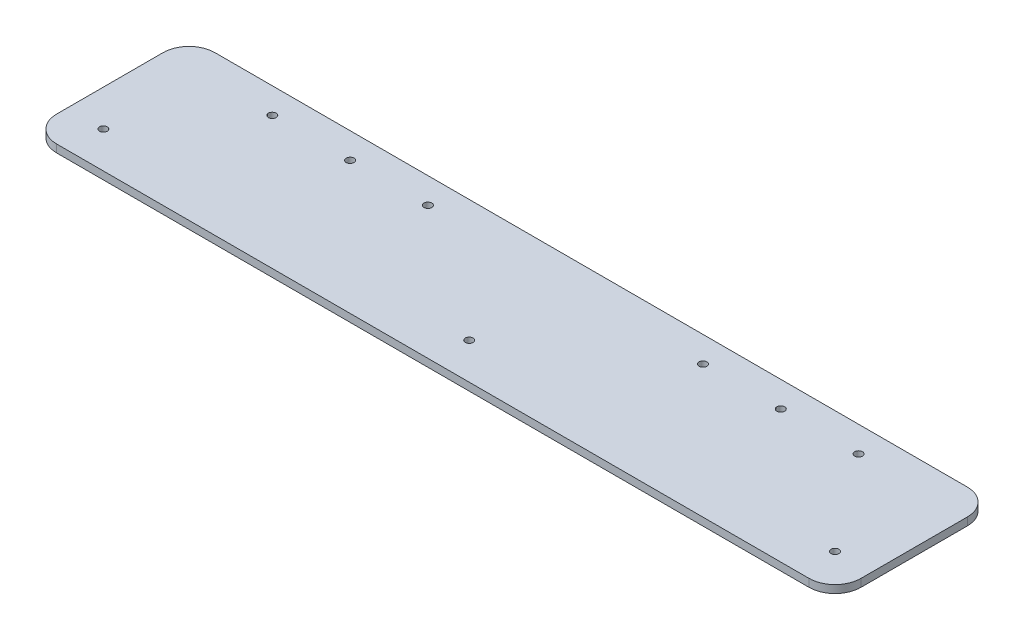
SolidWorks part; units mm, degrees
ref_plane "前视基准面" through (0, 0, 0) normal (0, 0, 1) x (1, 0, 0)
ref_plane "上视基准面" through (0, 0, 0) normal (0, 1, 0) x (1, 0, 0)
ref_plane "右视基准面" through (0, 0, 0) normal (1, 0, 0) x (0, 0, -1)
sketch "草图1" plane through (0, 0, 0) normal (0, 1, 0) x (1, 0, 0)
  line L0 (183.25, -128.5) -> (183.25, -131.5) construction
  line L1 (10, 0) -> (136.8844, 0) construction
  line L2 (0, -10) -> (0, -210) construction
  line L3 (10, -220) -> (300, -220)
  line L4 (310, -10) -> (310, -210) construction
  line L5 (28.75, -14.75) -> (47.25, -14.75) construction
  line L6 (28.75, -14.75) -> (28.75, -33.25) construction
  line L7 (28.75, -33.25) -> (47.25, -33.25) construction
  line L8 (173, -85) -> (173, 0) construction
  line L9 (173, -85) -> (310, -85) construction
  line L10 (190, -66) -> (190, 0) construction
  line L11 (215, -58) -> (215, 0) construction
  line L12 (241, -58) -> (241, 0) construction
  line L13 (247, -84) -> (247, 0) construction
  line L14 (222, -84) -> (222, 0) construction
  line L15 (0, -220) -> (310, 0) construction
  line L16 (241, -58) -> (310, -58) construction
  line L17 (247, -84) -> (310, -84) construction
  line L18 (215, -58) -> (310, -58) construction
  line L19 (222, -84) -> (310, -84) construction
  line L20 (190, -66) -> (310, -66) construction
  line L21 (310, -220) -> (0, 0) construction
  line L22 (141.1791, -3.5) -> (143.5, -3.5) construction
  line L23 (139.4291, -2.4682) -> (138.6344, -1.0318) construction
  line L24 (170.5709, -2.4682) -> (171.3656, -1.0318) construction
  line L25 (173.1156, 0) -> (300, 0) construction
  line L26 (155, -110) -> (155, -220) construction
  line L27 (47.25, -14.75) -> (47.25, -33.25) construction
  line L28 (28.75, -14.75) -> (47.25, -33.25) construction
  line L29 (28.75, -33.25) -> (47.25, -14.75) construction
  line L30 (52.75, -14.75) -> (71.25, -14.75) construction
  line L31 (52.75, -14.75) -> (52.75, -33.25) construction
  line L32 (52.75, -33.25) -> (71.25, -33.25) construction
  line L33 (71.25, -14.75) -> (71.25, -33.25) construction
  line L34 (52.75, -14.75) -> (71.25, -33.25) construction
  line L35 (52.75, -33.25) -> (71.25, -14.75) construction
  line L36 (76.75, -14.75) -> (95.25, -14.75) construction
  line L37 (76.75, -14.75) -> (76.75, -33.25) construction
  line L38 (76.75, -33.25) -> (95.25, -33.25) construction
  line L39 (95.25, -14.75) -> (95.25, -33.25) construction
  line L40 (76.75, -14.75) -> (95.25, -33.25) construction
  line L41 (76.75, -33.25) -> (95.25, -14.75) construction
  line L42 (100.75, -14.75) -> (119.25, -14.75) construction
  line L43 (100.75, -14.75) -> (100.75, -33.25) construction
  line L44 (100.75, -33.25) -> (119.25, -33.25) construction
  line L45 (119.25, -14.75) -> (119.25, -33.25) construction
  line L46 (100.75, -14.75) -> (119.25, -33.25) construction
  line L47 (100.75, -33.25) -> (119.25, -14.75) construction
  line L48 (188.75, -14.75) -> (207.25, -14.75) construction
  line L49 (188.75, -14.75) -> (188.75, -33.25) construction
  line L50 (188.75, -33.25) -> (207.25, -33.25) construction
  line L51 (207.25, -14.75) -> (207.25, -33.25) construction
  line L52 (188.75, -14.75) -> (207.25, -33.25) construction
  line L53 (188.75, -33.25) -> (207.25, -14.75) construction
  line L54 (212.75, -14.75) -> (231.25, -14.75) construction
  line L55 (212.75, -14.75) -> (212.75, -33.25) construction
  line L56 (212.75, -33.25) -> (231.25, -33.25) construction
  line L57 (231.25, -14.75) -> (231.25, -33.25) construction
  line L58 (212.75, -14.75) -> (231.25, -33.25) construction
  line L59 (212.75, -33.25) -> (231.25, -14.75) construction
  line L60 (236.75, -14.75) -> (255.25, -14.75) construction
  line L61 (236.75, -14.75) -> (236.75, -33.25) construction
  line L62 (236.75, -33.25) -> (255.25, -33.25) construction
  line L63 (255.25, -14.75) -> (255.25, -33.25) construction
  line L64 (236.75, -14.75) -> (255.25, -33.25) construction
  line L65 (236.75, -33.25) -> (255.25, -14.75) construction
  line L66 (260.75, -14.75) -> (279.25, -14.75) construction
  line L67 (260.75, -14.75) -> (260.75, -33.25) construction
  line L68 (260.75, -33.25) -> (279.25, -33.25) construction
  line L69 (279.25, -14.75) -> (279.25, -33.25) construction
  line L70 (260.75, -14.75) -> (279.25, -33.25) construction
  line L71 (260.75, -33.25) -> (279.25, -14.75) construction
  line L72 (183, -123) -> (197, -123) construction
  line L73 (183, -123) -> (183, -128.25) construction
  line L74 (183, -137) -> (197, -137) construction
  line L75 (197, -123) -> (197, -128.25) construction
  line L76 (183, -123) -> (197, -137) construction
  line L77 (183, -137) -> (197, -123) construction
  line L78 (183.25, -128.5) -> (183, -128.25) construction
  line L79 (183.25, -131.5) -> (183, -131.75) construction
  line L80 (196.75, -128.5) -> (196.75, -131.5) construction
  line L81 (196.75, -128.5) -> (197, -128.25) construction
  line L82 (196.75, -131.5) -> (197, -131.75) construction
  line L83 (183, -131.75) -> (183, -137) construction
  line L84 (197, -131.75) -> (197, -137) construction
  line L85 (31.25, -22.5) -> (31.25, -25.5) construction
  line L86 (31, -17) -> (45, -17) construction
  line L87 (31, -17) -> (31, -22.25) construction
  line L88 (31, -31) -> (45, -31) construction
  line L89 (45, -17) -> (45, -22.25) construction
  line L90 (31, -17) -> (45, -31) construction
  line L91 (31, -31) -> (45, -17) construction
  line L92 (31.25, -22.5) -> (31, -22.25) construction
  line L93 (31.25, -25.5) -> (31, -25.75) construction
  line L94 (44.75, -22.5) -> (44.75, -25.5) construction
  line L95 (44.75, -22.5) -> (45, -22.25) construction
  line L96 (44.75, -25.5) -> (45, -25.75) construction
  line L97 (31, -25.75) -> (31, -31) construction
  line L98 (45, -25.75) -> (45, -31) construction
  line L99 (55.25, -22.5) -> (55.25, -25.5) construction
  line L100 (55, -17) -> (69, -17) construction
  line L101 (55, -17) -> (55, -22.25) construction
  line L102 (55, -31) -> (69, -31) construction
  line L103 (69, -17) -> (69, -22.25) construction
  line L104 (55, -17) -> (69, -31) construction
  line L105 (55, -31) -> (69, -17) construction
  line L106 (55.25, -22.5) -> (55, -22.25) construction
  line L107 (55.25, -25.5) -> (55, -25.75) construction
  line L108 (68.75, -22.5) -> (68.75, -25.5) construction
  line L109 (68.75, -22.5) -> (69, -22.25) construction
  line L110 (68.75, -25.5) -> (69, -25.75) construction
  line L111 (55, -25.75) -> (55, -31) construction
  line L112 (69, -25.75) -> (69, -31) construction
  line L113 (79.25, -22.5) -> (79.25, -25.5) construction
  line L114 (79, -17) -> (93, -17) construction
  line L115 (79, -17) -> (79, -22.25) construction
  line L116 (79, -31) -> (93, -31) construction
  line L117 (93, -17) -> (93, -22.25) construction
  line L118 (79, -17) -> (93, -31) construction
  line L119 (79, -31) -> (93, -17) construction
  line L120 (79.25, -22.5) -> (79, -22.25) construction
  line L121 (79.25, -25.5) -> (79, -25.75) construction
  line L122 (92.75, -22.5) -> (92.75, -25.5) construction
  line L123 (92.75, -22.5) -> (93, -22.25) construction
  line L124 (92.75, -25.5) -> (93, -25.75) construction
  line L125 (79, -25.75) -> (79, -31) construction
  line L126 (93, -25.75) -> (93, -31) construction
  line L127 (103.25, -22.5) -> (103.25, -25.5) construction
  line L128 (103, -17) -> (117, -17) construction
  line L129 (103, -17) -> (103, -22.25) construction
  line L130 (103, -31) -> (117, -31) construction
  line L131 (117, -17) -> (117, -22.25) construction
  line L132 (103, -17) -> (117, -31) construction
  line L133 (103, -31) -> (117, -17) construction
  line L134 (103.25, -22.5) -> (103, -22.25) construction
  line L135 (103.25, -25.5) -> (103, -25.75) construction
  line L136 (116.75, -22.5) -> (116.75, -25.5) construction
  line L137 (116.75, -22.5) -> (117, -22.25) construction
  line L138 (116.75, -25.5) -> (117, -25.75) construction
  line L139 (103, -25.75) -> (103, -31) construction
  line L140 (117, -25.75) -> (117, -31) construction
  line L141 (191.25, -22.5) -> (191.25, -25.5) construction
  line L142 (191, -17) -> (205, -17) construction
  line L143 (191, -17) -> (191, -22.25) construction
  line L144 (191, -31) -> (205, -31) construction
  line L145 (205, -17) -> (205, -22.25) construction
  line L146 (191, -17) -> (205, -31) construction
  line L147 (191, -31) -> (205, -17) construction
  line L148 (191.25, -22.5) -> (191, -22.25) construction
  line L149 (191.25, -25.5) -> (191, -25.75) construction
  line L150 (204.75, -22.5) -> (204.75, -25.5) construction
  line L151 (204.75, -22.5) -> (205, -22.25) construction
  line L152 (204.75, -25.5) -> (205, -25.75) construction
  line L153 (191, -25.75) -> (191, -31) construction
  line L154 (205, -25.75) -> (205, -31) construction
  line L155 (215.25, -22.5) -> (215.25, -25.5) construction
  line L156 (215, -17) -> (229, -17) construction
  line L157 (215, -17) -> (215, -22.25) construction
  line L158 (215, -31) -> (229, -31) construction
  line L159 (229, -17) -> (229, -22.25) construction
  line L160 (215, -17) -> (229, -31) construction
  line L161 (215, -31) -> (229, -17) construction
  line L162 (215.25, -22.5) -> (215, -22.25) construction
  line L163 (215.25, -25.5) -> (215, -25.75) construction
  line L164 (228.75, -22.5) -> (228.75, -25.5) construction
  line L165 (228.75, -22.5) -> (229, -22.25) construction
  line L166 (228.75, -25.5) -> (229, -25.75) construction
  line L167 (215, -25.75) -> (215, -31) construction
  line L168 (229, -25.75) -> (229, -31) construction
  line L169 (239.25, -22.5) -> (239.25, -25.5) construction
  line L170 (239, -17) -> (253, -17) construction
  line L171 (239, -17) -> (239, -22.25) construction
  line L172 (239, -31) -> (253, -31) construction
  line L173 (253, -17) -> (253, -22.25) construction
  line L174 (239, -17) -> (253, -31) construction
  line L175 (239, -31) -> (253, -17) construction
  line L176 (239.25, -22.5) -> (239, -22.25) construction
  line L177 (239.25, -25.5) -> (239, -25.75) construction
  line L178 (252.75, -22.5) -> (252.75, -25.5) construction
  line L179 (252.75, -22.5) -> (253, -22.25) construction
  line L180 (252.75, -25.5) -> (253, -25.75) construction
  line L181 (239, -25.75) -> (239, -31) construction
  line L182 (253, -25.75) -> (253, -31) construction
  line L183 (263.25, -22.5) -> (263.25, -25.5) construction
  line L184 (263, -17) -> (277, -17) construction
  line L185 (263, -17) -> (263, -22.25) construction
  line L186 (263, -31) -> (277, -31) construction
  line L187 (277, -17) -> (277, -22.25) construction
  line L188 (263, -17) -> (277, -31) construction
  line L189 (263, -31) -> (277, -17) construction
  line L190 (263.25, -22.5) -> (263, -22.25) construction
  line L191 (263.25, -25.5) -> (263, -25.75) construction
  line L192 (276.75, -22.5) -> (276.75, -25.5) construction
  line L193 (276.75, -22.5) -> (277, -22.25) construction
  line L194 (276.75, -25.5) -> (277, -25.75) construction
  line L195 (263, -25.75) -> (263, -31) construction
  line L196 (277, -25.75) -> (277, -31) construction
  line L197 (259.25, -64.5) -> (259.25, -67.5) construction
  line L198 (259, -59) -> (273, -59) construction
  line L199 (259, -59) -> (259, -64.25) construction
  line L200 (259, -73) -> (273, -73) construction
  line L201 (273, -59) -> (273, -64.25) construction
  line L202 (259, -59) -> (273, -73) construction
  line L203 (259, -73) -> (273, -59) construction
  line L204 (259.25, -64.5) -> (259, -64.25) construction
  line L205 (259.25, -67.5) -> (259, -67.75) construction
  line L206 (272.75, -64.5) -> (272.75, -67.5) construction
  line L207 (272.75, -64.5) -> (273, -64.25) construction
  line L208 (272.75, -67.5) -> (273, -67.75) construction
  line L209 (259, -67.75) -> (259, -73) construction
  line L210 (273, -67.75) -> (273, -73) construction
  line L211 (240.25, -82.5) -> (240.25, -85.5) construction
  line L212 (240, -77) -> (254, -77) construction
  line L213 (240, -77) -> (240, -82.25) construction
  line L214 (240, -91) -> (254, -91) construction
  line L215 (254, -77) -> (254, -82.25) construction
  line L216 (240, -77) -> (254, -91) construction
  line L217 (240, -91) -> (254, -77) construction
  line L218 (240.25, -82.5) -> (240, -82.25) construction
  line L219 (240.25, -85.5) -> (240, -85.75) construction
  line L220 (253.75, -82.5) -> (253.75, -85.5) construction
  line L221 (253.75, -82.5) -> (254, -82.25) construction
  line L222 (253.75, -85.5) -> (254, -85.75) construction
  line L223 (240, -85.75) -> (240, -91) construction
  line L224 (254, -85.75) -> (254, -91) construction
  line L225 (234.25, -56.5) -> (234.25, -59.5) construction
  line L226 (234, -51) -> (248, -51) construction
  line L227 (234, -51) -> (234, -56.25) construction
  line L228 (234, -65) -> (248, -65) construction
  line L229 (248, -51) -> (248, -56.25) construction
  line L230 (234, -51) -> (248, -65) construction
  line L231 (234, -65) -> (248, -51) construction
  line L232 (234.25, -56.5) -> (234, -56.25) construction
  line L233 (234.25, -59.5) -> (234, -59.75) construction
  line L234 (247.75, -56.5) -> (247.75, -59.5) construction
  line L235 (247.75, -56.5) -> (248, -56.25) construction
  line L236 (247.75, -59.5) -> (248, -59.75) construction
  line L237 (234, -59.75) -> (234, -65) construction
  line L238 (248, -59.75) -> (248, -65) construction
  line L239 (215.25, -82.5) -> (215.25, -85.5) construction
  line L240 (215, -77) -> (229, -77) construction
  line L241 (215, -77) -> (215, -82.25) construction
  line L242 (215, -91) -> (229, -91) construction
  line L243 (229, -77) -> (229, -82.25) construction
  line L244 (215, -77) -> (229, -91) construction
  line L245 (215, -91) -> (229, -77) construction
  line L246 (215.25, -82.5) -> (215, -82.25) construction
  line L247 (215.25, -85.5) -> (215, -85.75) construction
  line L248 (228.75, -82.5) -> (228.75, -85.5) construction
  line L249 (228.75, -82.5) -> (229, -82.25) construction
  line L250 (228.75, -85.5) -> (229, -85.75) construction
  line L251 (215, -85.75) -> (215, -91) construction
  line L252 (229, -85.75) -> (229, -91) construction
  line L253 (29.25, -95.5) -> (29.25, -98.5) construction
  line L254 (29, -90) -> (43, -90) construction
  line L255 (29, -90) -> (29, -95.25) construction
  line L256 (29, -104) -> (43, -104) construction
  line L257 (43, -90) -> (43, -95.25) construction
  line L258 (29, -90) -> (43, -104) construction
  line L259 (29, -104) -> (43, -90) construction
  line L260 (29.25, -95.5) -> (29, -95.25) construction
  line L261 (29.25, -98.5) -> (29, -98.75) construction
  line L262 (42.75, -95.5) -> (42.75, -98.5) construction
  line L263 (42.75, -95.5) -> (43, -95.25) construction
  line L264 (42.75, -98.5) -> (43, -98.75) construction
  line L265 (29, -98.75) -> (29, -104) construction
  line L266 (43, -98.75) -> (43, -104) construction
  line L267 (51.25, -78.5) -> (51.25, -81.5) construction
  line L268 (51, -73) -> (65, -73) construction
  line L269 (51, -73) -> (51, -78.25) construction
  line L270 (51, -87) -> (65, -87) construction
  line L271 (65, -73) -> (65, -78.25) construction
  line L272 (51, -73) -> (65, -87) construction
  line L273 (51, -87) -> (65, -73) construction
  line L274 (51.25, -78.5) -> (51, -78.25) construction
  line L275 (51.25, -81.5) -> (51, -81.75) construction
  line L276 (64.75, -78.5) -> (64.75, -81.5) construction
  line L277 (64.75, -78.5) -> (65, -78.25) construction
  line L278 (64.75, -81.5) -> (65, -81.75) construction
  line L279 (51, -81.75) -> (51, -87) construction
  line L280 (65, -81.75) -> (65, -87) construction
  line L281 (77.25, -75.5) -> (77.25, -78.5) construction
  line L282 (77, -70) -> (91, -70) construction
  line L283 (77, -70) -> (77, -75.25) construction
  line L284 (77, -84) -> (91, -84) construction
  line L285 (91, -70) -> (91, -75.25) construction
  line L286 (77, -70) -> (91, -84) construction
  line L287 (77, -84) -> (91, -70) construction
  line L288 (77.25, -75.5) -> (77, -75.25) construction
  line L289 (77.25, -78.5) -> (77, -78.75) construction
  line L290 (90.75, -75.5) -> (90.75, -78.5) construction
  line L291 (90.75, -75.5) -> (91, -75.25) construction
  line L292 (90.75, -78.5) -> (91, -78.75) construction
  line L293 (77, -78.75) -> (77, -84) construction
  line L294 (91, -78.75) -> (91, -84) construction
  line L295 (82.25, -51.5) -> (82.25, -54.5) construction
  line L296 (82, -46) -> (96, -46) construction
  line L297 (82, -46) -> (82, -51.25) construction
  line L298 (82, -60) -> (96, -60) construction
  line L299 (96, -46) -> (96, -51.25) construction
  line L300 (82, -46) -> (96, -60) construction
  line L301 (82, -60) -> (96, -46) construction
  line L302 (82.25, -51.5) -> (82, -51.25) construction
  line L303 (82.25, -54.5) -> (82, -54.75) construction
  line L304 (95.75, -51.5) -> (95.75, -54.5) construction
  line L305 (95.75, -51.5) -> (96, -51.25) construction
  line L306 (95.75, -54.5) -> (96, -54.75) construction
  line L307 (82, -54.75) -> (82, -60) construction
  line L308 (96, -54.75) -> (96, -60) construction
  line L309 (99.25, -88.5) -> (99.25, -91.5) construction
  line L310 (99, -83) -> (113, -83) construction
  line L311 (99, -83) -> (99, -88.25) construction
  line L312 (99, -97) -> (113, -97) construction
  line L313 (113, -83) -> (113, -88.25) construction
  line L314 (99, -83) -> (113, -97) construction
  line L315 (99, -97) -> (113, -83) construction
  line L316 (99.25, -88.5) -> (99, -88.25) construction
  line L317 (99.25, -91.5) -> (99, -91.75) construction
  line L318 (112.75, -88.5) -> (112.75, -91.5) construction
  line L319 (112.75, -88.5) -> (113, -88.25) construction
  line L320 (112.75, -91.5) -> (113, -91.75) construction
  line L321 (99, -91.75) -> (99, -97) construction
  line L322 (113, -91.75) -> (113, -97) construction
  line L323 (208.25, -56.5) -> (208.25, -59.5) construction
  line L324 (208, -51) -> (222, -51) construction
  line L325 (208, -51) -> (208, -56.25) construction
  line L326 (208, -65) -> (222, -65) construction
  line L327 (222, -51) -> (222, -56.25) construction
  line L328 (208, -51) -> (222, -65) construction
  line L329 (208, -65) -> (222, -51) construction
  line L330 (208.25, -56.5) -> (208, -56.25) construction
  line L331 (208.25, -59.5) -> (208, -59.75) construction
  line L332 (221.75, -56.5) -> (221.75, -59.5) construction
  line L333 (221.75, -56.5) -> (222, -56.25) construction
  line L334 (221.75, -59.5) -> (222, -59.75) construction
  line L335 (208, -59.75) -> (208, -65) construction
  line L336 (222, -59.75) -> (222, -65) construction
  line L337 (183.25, -64.5) -> (183.25, -67.5) construction
  line L338 (183, -59) -> (197, -59) construction
  line L339 (183, -59) -> (183, -64.25) construction
  line L340 (183, -73) -> (197, -73) construction
  line L341 (197, -59) -> (197, -64.25) construction
  line L342 (183, -59) -> (197, -73) construction
  line L343 (183, -73) -> (197, -59) construction
  line L344 (183.25, -64.5) -> (183, -64.25) construction
  line L345 (183.25, -67.5) -> (183, -67.75) construction
  line L346 (196.75, -64.5) -> (196.75, -67.5) construction
  line L347 (196.75, -64.5) -> (197, -64.25) construction
  line L348 (196.75, -67.5) -> (197, -67.75) construction
  line L349 (183, -67.75) -> (183, -73) construction
  line L350 (197, -67.75) -> (197, -73) construction
  line L351 (191.25, -88.5) -> (191.25, -91.5) construction
  line L352 (191, -83) -> (205, -83) construction
  line L353 (191, -83) -> (191, -88.25) construction
  line L354 (191, -97) -> (205, -97) construction
  line L355 (205, -83) -> (205, -88.25) construction
  line L356 (191, -83) -> (205, -97) construction
  line L357 (191, -97) -> (205, -83) construction
  line L358 (191.25, -88.5) -> (191, -88.25) construction
  line L359 (191.25, -91.5) -> (191, -91.75) construction
  line L360 (204.75, -88.5) -> (204.75, -91.5) construction
  line L361 (204.75, -88.5) -> (205, -88.25) construction
  line L362 (204.75, -91.5) -> (205, -91.75) construction
  line L363 (191, -91.75) -> (191, -97) construction
  line L364 (205, -91.75) -> (205, -97) construction
  line L365 (166.25, -83.5) -> (166.25, -86.5) construction
  line L366 (166, -78) -> (180, -78) construction
  line L367 (166, -78) -> (166, -83.25) construction
  line L368 (166, -92) -> (180, -92) construction
  line L369 (180, -78) -> (180, -83.25) construction
  line L370 (166, -78) -> (180, -92) construction
  line L371 (166, -92) -> (180, -78) construction
  line L372 (166.25, -83.5) -> (166, -83.25) construction
  line L373 (166.25, -86.5) -> (166, -86.75) construction
  line L374 (179.75, -83.5) -> (179.75, -86.5) construction
  line L375 (179.75, -83.5) -> (180, -83.25) construction
  line L376 (179.75, -86.5) -> (180, -86.75) construction
  line L377 (166, -86.75) -> (166, -92) construction
  line L378 (180, -86.75) -> (180, -92) construction
  line L379 (107.25, -128.5) -> (107.25, -131.5) construction
  line L380 (107, -123) -> (121, -123) construction
  line L381 (107, -123) -> (107, -128.25) construction
  line L382 (107, -137) -> (121, -137) construction
  line L383 (121, -123) -> (121, -128.25) construction
  line L384 (107, -123) -> (121, -137) construction
  line L385 (107, -137) -> (121, -123) construction
  line L386 (107.25, -128.5) -> (107, -128.25) construction
  line L387 (107.25, -131.5) -> (107, -131.75) construction
  line L388 (120.75, -128.5) -> (120.75, -131.5) construction
  line L389 (120.75, -128.5) -> (121, -128.25) construction
  line L390 (120.75, -131.5) -> (121, -131.75) construction
  line L391 (107, -131.75) -> (107, -137) construction
  line L392 (121, -131.75) -> (121, -137) construction
  line L393 (138.25, -136.5) -> (138.25, -139.5) construction
  line L394 (138, -131) -> (152, -131) construction
  line L395 (138, -131) -> (138, -136.25) construction
  line L396 (138, -145) -> (152, -145) construction
  line L397 (152, -131) -> (152, -136.25) construction
  line L398 (138, -131) -> (152, -145) construction
  line L399 (138, -145) -> (152, -131) construction
  line L400 (138.25, -136.5) -> (138, -136.25) construction
  line L401 (138.25, -139.5) -> (138, -139.75) construction
  line L402 (151.75, -136.5) -> (151.75, -139.5) construction
  line L403 (151.75, -136.5) -> (152, -136.25) construction
  line L404 (151.75, -139.5) -> (152, -139.75) construction
  line L405 (138, -139.75) -> (138, -145) construction
  line L406 (152, -139.75) -> (152, -145) construction
  line L407 (166.5, -3.5) -> (168.8209, -3.5) construction
  line L409 (143.5, -3.5) -> (143.5, -55.5) construction
  line L410 (143.5, -55.5) -> (166.5, -55.5) construction
  line L411 (166.5, -3.5) -> (166.5, -55.5) construction
  line L412 (143.5, -3.5) -> (166.5, -55.5) construction
  line L413 (143.5, -55.5) -> (166.5, -3.5) construction
  line L414 (143.5, -3.5) -> (166.5, -3.5) construction
  line L415 (10, -159) -> (300, -159)
  line L416 (0, -169) -> (0, -210)
  line L417 (310, -169) -> (310, -210)
  arc A0 (10, 0) -> (0, -10) centre (10, -10) ccw construction
  arc A1 (0, -210) -> (10, -220) centre (10, -210) ccw
  arc A2 (300, -220) -> (310, -210) centre (300, -210) ccw
  arc A3 (300, 0) -> (310, -10) centre (300, -10) cw construction
  circle A8 centre (173, -85) radius 11 construction
  circle A9 centre (190, -66) radius 11 construction
  circle A11 centre (215, -58) radius 11 construction
  circle A12 centre (222, -84) radius 11 construction
  circle A13 centre (247, -84) radius 11 construction
  circle A14 centre (241, -58) radius 11 construction
  circle A15 centre (14, -14) radius 1.5 construction
  circle A16 centre (14, -206) radius 1.5
  circle A17 centre (296, -206) radius 1.5
  circle A18 centre (296, -12.2857) radius 1.5 construction
  arc A19 (173.1156, 0) -> (171.3656, -1.0318) centre (173.1156, -2) ccw construction
  arc A20 (170.5709, -2.4682) -> (168.8209, -3.5) centre (168.8209, -1.5) cw construction
  arc A21 (141.1791, -3.5) -> (139.4291, -2.4682) centre (141.1791, -1.5) cw construction
  arc A22 (136.8844, 0) -> (138.6344, -1.0318) centre (136.8844, -2) cw construction
  circle A24 centre (198, -90) radius 11 construction
  circle A25 centre (114, -130) radius 13.5 construction
  circle A26 centre (190, -130) radius 13.5 construction
  circle A27 centre (155, -206) radius 1.5
  circle A28 centre (175, -14) radius 1.5 construction
  circle A29 centre (145, -138) radius 11 construction
  circle A30 centre (106, -90) radius 11 construction
  circle A31 centre (84, -77) radius 11 construction
  circle A32 centre (58, -80) radius 11 construction
  circle A33 centre (36, -97) radius 11 construction
  circle A34 centre (89, -53) radius 11 construction
  circle A35 centre (266, -66) radius 11 construction
  circle A36 centre (110, -24) radius 4.5 construction
  circle A37 centre (86, -24) radius 4.5 construction
  circle A38 centre (62, -24) radius 4.5 construction
  circle A39 centre (38, -24) radius 4.5 construction
  circle A40 centre (198, -24) radius 4.5 construction
  circle A41 centre (222, -24) radius 4.5 construction
  circle A42 centre (246, -24) radius 4.5 construction
  circle A43 centre (270, -24) radius 4.5 construction
  circle A48 centre (135, -14) radius 1.5 construction
  circle A51 centre (296, -110) radius 1.5 construction
  circle A52 centre (14, -110) radius 1.5 construction
  circle A53 centre (155, -110) radius 1.5 construction
  circle A54 centre (72, -110) radius 1.5 construction
  circle A55 centre (72, -168.9032) radius 1.5
  circle A56 centre (72, -51.0968) radius 1.5 construction
  circle A57 centre (42, -168.9032) radius 1.5
  circle A58 centre (102, -168.9032) radius 1.5
  circle A59 centre (238, -110) radius 1.5 construction
  circle A60 centre (238, -168.9032) radius 1.5
  circle A61 centre (268, -168.9032) radius 1.5
  circle A62 centre (208, -168.9032) radius 1.5
  circle A63 centre (246, -39) radius 1.5 construction
  circle A64 centre (198, -39) radius 1.5 construction
  circle A65 centre (110, -70) radius 1.5 construction
  circle A66 centre (38, -51.0968) radius 1.5 construction
  circle A67 centre (198, -110) radius 1.5 construction
  circle A68 centre (143.5, -90) radius 1.5 construction
  arc A69 (10, -159) -> (0, -169) centre (10, -169) ccw
  arc A70 (310, -169) -> (300, -159) centre (300, -169) ccw
  point P8 (0, 0)
  point P12 (0, -220)
  point P15 (310, -220)
  point P18 (310, 0)
  point P70 (171.9365, 0)
  point P73 (170, -3.5)
  point P76 (140, -3.5)
  point P79 (138.0635, 0)
  point P147 (190, -130)
  point P152 (155, -29.5)
  point P155 (183.25, -130)
  point P160 (196.75, -130)
  point P163 (38, -24)
  point P170 (31.25, -24)
  point P175 (44.75, -24)
  point P180 (62, -24)
  point P187 (55.25, -24)
  point P192 (68.75, -24)
  point P196 (86, -24)
  point P203 (79.25, -24)
  point P208 (92.75, -24)
  point P213 (110, -24)
  point P220 (103.25, -24)
  point P225 (116.75, -24)
  point P229 (198, -24)
  point P236 (191.25, -24)
  point P241 (204.75, -24)
  point P245 (222, -24)
  point P252 (215.25, -24)
  point P257 (228.75, -24)
  point P261 (246, -24)
  point P268 (239.25, -24)
  point P273 (252.75, -24)
  point P277 (270, -24)
  point P284 (263.25, -24)
  point P289 (276.75, -24)
  point P293 (266, -66)
  point P300 (259.25, -66)
  point P305 (272.75, -66)
  point P310 (247, -84)
  point P317 (240.25, -84)
  point P322 (253.75, -84)
  point P326 (241, -58)
  point P333 (234.25, -58)
  point P338 (247.75, -58)
  point P342 (222, -84)
  point P349 (215.25, -84)
  point P354 (228.75, -84)
  point P358 (36, -97)
  point P365 (29.25, -97)
  point P370 (42.75, -97)
  point P374 (58, -80)
  point P381 (51.25, -80)
  point P386 (64.75, -80)
  point P389 (0, -159)
  point P390 (84, -77)
  point P397 (77.25, -77)
  point P402 (90.75, -77)
  point P407 (89, -53)
  point P414 (82.25, -53)
  point P419 (95.75, -53)
  point P422 (310, -159)
  point P423 (106, -90)
  point P430 (99.25, -90)
  point P435 (112.75, -90)
  point P439 (215, -58)
  point P446 (208.25, -58)
  point P451 (221.75, -58)
  point P455 (190, -66)
  point P462 (183.25, -66)
  point P467 (196.75, -66)
  point P471 (198, -90)
  point P478 (191.25, -90)
  point P483 (204.75, -90)
  point P492 (173, -85)
  point P499 (166.25, -85)
  point P504 (179.75, -85)
  point P508 (114, -130)
  point P515 (107.25, -130)
  point P520 (120.75, -130)
  point P524 (145, -138)
  point P531 (138.25, -138)
  point P536 (151.75, -138)
  dimension "D3" = 10
  dimension "D7" = 90
  dimension "D10" = 22
  dimension "D15" = 53
  dimension "D16" = 22
  dimension "D19" = 22
  dimension "D20" = 22
  dimension "D21" = 22
  dimension "D22" = 84
  dimension "D23" = 22
  dimension "D24" = 22
  dimension "D32" = 22
  dimension "D34" = 3
  dimension "D37" = 3
  dimension "D40" = 3
  dimension "D43" = 3
  dimension "D47" = 3.5
  dimension "D50" = 140
  dimension "D51" = 2
  dimension "D52" = 90
  dimension "D54" = 27
  dimension "D56" = 27
  dimension "D59" = 3
  dimension "D61" = 14
  dimension "D62" = 3
  dimension "D64" = 22
  dimension "D8" = 22
  dimension "D9" = 22
  dimension "D11" = 22
  dimension "D12" = 22
  dimension "D13" = 22
  dimension "D76" = 9
  dimension "D84" = 9
  dimension "D86" = 3
  dimension "D89" = 18.5
  dimension "D92" = 18.5
  dimension "D95" = 18.5
  dimension "D98" = 3
  dimension "D101" = 18.5
  dimension "D103" = 18.5
  dimension "D87" = 3
  dimension "D301" = 3
  dimension "D302" = 3
  dimension "D304" = 3
  dimension "D305" = 3
  dimension "D306" = 3
  dimension "D308" = 3
  dimension "D310" = 3
  dimension "D312" = 3
  dimension "D313" = 3
  dimension "D314" = 3
  dimension "D317" = 3
  dimension "D319" = 3
  dimension "D321" = 3
  dimension "D323" = 3
  dimension "D324" = 3
  dimension "D325" = 3
  dimension "D327" = 10
  dimension "D328" = 10
  dimension "D1" = 220
  dimension "D2" = 310
  dimension "D14" = 89
  dimension "D17" = 85
  dimension "D18" = 137
  dimension "D25" = 66
  dimension "D26" = 120
  dimension "D27" = 36
  dimension "D28" = 58
  dimension "D29" = 95
  dimension "D30" = 88
  dimension "D31" = 69
  dimension "D33" = 63
  dimension "D35" = 14
  dimension "D36" = 14
  dimension "D38" = 14
  dimension "D39" = 14
  dimension "D41" = 14
  dimension "D42" = 14
  dimension "D44" = 14
  dimension "D45" = 12.2857
  dimension "D46" = 4
  dimension "D48" = 30
  dimension "D49" = 4
  dimension "D53" = 112
  dimension "D55" = 114
  dimension "D57" = 90
  dimension "D58" = 120
  dimension "D60" = 14
  dimension "D63" = 135
  dimension "D65" = 82
  dimension "D66" = 145
  dimension "D67" = 97
  dimension "D68" = 80
  dimension "D69" = 58
  dimension "D70" = 84
  dimension "D71" = 77
  dimension "D72" = 90
  dimension "D73" = 106
  dimension "D74" = 44
  dimension "D75" = 66
  dimension "D78" = 24
  dimension "D79" = 110
  dimension "D80" = 24
  dimension "D82" = 24
  dimension "D83" = 24
  dimension "D85" = 40
  dimension "D88" = 18.5
  dimension "D90" = 18.5
  dimension "D91" = 18.5
  dimension "D93" = 18.5
  dimension "D94" = 18.5
  dimension "D96" = 18.5
  dimension "D97" = 18.5
  dimension "D99" = 14
  dimension "D100" = 135
  dimension "D102" = 18.5
  dimension "D104" = 18.5
  dimension "D105" = 18.5
  dimension "D106" = 18.5
  dimension "D107" = 14
  dimension "D108" = 14
  dimension "D109" = 0.25
  dimension "D110" = 3
  dimension "D111" = 135
  dimension "D112" = 3
  dimension "D113" = 0.25
  dimension "D114" = 135
  dimension "D115" = 14
  dimension "D116" = 14
  dimension "D117" = 0.25
  dimension "D118" = 3
  dimension "D119" = 135
  dimension "D120" = 3
  dimension "D121" = 0.25
  dimension "D122" = 135
  dimension "D123" = 14
  dimension "D124" = 14
  dimension "D125" = 0.25
  dimension "D126" = 3
  dimension "D127" = 135
  dimension "D128" = 3
  dimension "D129" = 0.25
  dimension "D130" = 135
  dimension "D131" = 14
  dimension "D132" = 14
  dimension "D133" = 0.25
  dimension "D134" = 3
  dimension "D135" = 135
  dimension "D136" = 3
  dimension "D137" = 0.25
  dimension "D138" = 135
  dimension "D139" = 14
  dimension "D140" = 14
  dimension "D141" = 0.25
  dimension "D142" = 3
  dimension "D143" = 135
  dimension "D144" = 3
  dimension "D145" = 0.25
  dimension "D146" = 135
  dimension "D147" = 14
  dimension "D148" = 14
  dimension "D149" = 0.25
  dimension "D150" = 3
  dimension "D151" = 135
  dimension "D152" = 3
  dimension "D153" = 0.25
  dimension "D154" = 135
  dimension "D155" = 14
  dimension "D156" = 14
  dimension "D157" = 0.25
  dimension "D158" = 3
  dimension "D159" = 135
  dimension "D160" = 3
  dimension "D161" = 0.25
  dimension "D162" = 135
  dimension "D163" = 14
  dimension "D164" = 14
  dimension "D165" = 0.25
  dimension "D166" = 3
  dimension "D167" = 135
  dimension "D168" = 3
  dimension "D169" = 0.25
  dimension "D170" = 135
  dimension "D171" = 14
  dimension "D172" = 14
  dimension "D173" = 0.25
  dimension "D174" = 3
  dimension "D175" = 135
  dimension "D176" = 3
  dimension "D177" = 0.25
  dimension "D178" = 135
  dimension "D179" = 14
  dimension "D180" = 14
  dimension "D181" = 0.25
  dimension "D182" = 3
  dimension "D183" = 135
  dimension "D184" = 3
  dimension "D185" = 0.25
  dimension "D186" = 135
  dimension "D187" = 14
  dimension "D188" = 14
  dimension "D189" = 0.25
  dimension "D190" = 3
  dimension "D191" = 135
  dimension "D192" = 3
  dimension "D193" = 0.25
  dimension "D194" = 135
  dimension "D195" = 14
  dimension "D196" = 14
  dimension "D197" = 0.25
  dimension "D198" = 3
  dimension "D199" = 135
  dimension "D200" = 3
  dimension "D201" = 0.25
  dimension "D202" = 135
  dimension "D203" = 14
  dimension "D204" = 14
  dimension "D205" = 0.25
  dimension "D206" = 3
  dimension "D207" = 135
  dimension "D208" = 3
  dimension "D209" = 0.25
  dimension "D210" = 135
  dimension "D211" = 14
  dimension "D212" = 14
  dimension "D213" = 0.25
  dimension "D214" = 3
  dimension "D215" = 135
  dimension "D216" = 3
  dimension "D217" = 0.25
  dimension "D218" = 135
  dimension "D219" = 14
  dimension "D220" = 14
  dimension "D221" = 0.25
  dimension "D222" = 3
  dimension "D223" = 135
  dimension "D224" = 3
  dimension "D225" = 0.25
  dimension "D226" = 135
  dimension "D227" = 14
  dimension "D228" = 14
  dimension "D229" = 0.25
  dimension "D230" = 3
  dimension "D231" = 135
  dimension "D232" = 3
  dimension "D233" = 0.25
  dimension "D234" = 135
  dimension "D235" = 14
  dimension "D236" = 14
  dimension "D237" = 0.25
  dimension "D238" = 3
  dimension "D239" = 135
  dimension "D240" = 3
  dimension "D241" = 0.25
  dimension "D242" = 135
  dimension "D243" = 14
  dimension "D244" = 14
  dimension "D245" = 0.25
  dimension "D246" = 3
  dimension "D247" = 135
  dimension "D248" = 3
  dimension "D249" = 0.25
  dimension "D250" = 135
  dimension "D251" = 14
  dimension "D252" = 14
  dimension "D253" = 0.25
  dimension "D254" = 3
  dimension "D255" = 135
  dimension "D256" = 3
  dimension "D257" = 0.25
  dimension "D258" = 135
  dimension "D259" = 14
  dimension "D260" = 14
  dimension "D261" = 0.25
  dimension "D262" = 3
  dimension "D263" = 135
  dimension "D264" = 3
  dimension "D265" = 0.25
  dimension "D266" = 135
  dimension "D267" = 14
  dimension "D268" = 14
  dimension "D269" = 0.25
  dimension "D270" = 3
  dimension "D271" = 135
  dimension "D272" = 3
  dimension "D273" = 0.25
  dimension "D274" = 135
  dimension "D275" = 14
  dimension "D276" = 14
  dimension "D277" = 0.25
  dimension "D278" = 3
  dimension "D279" = 135
  dimension "D280" = 3
  dimension "D281" = 0.25
  dimension "D282" = 135
  dimension "D283" = 14
  dimension "D284" = 14
  dimension "D285" = 0.25
  dimension "D286" = 3
  dimension "D287" = 135
  dimension "D288" = 3
  dimension "D289" = 0.25
  dimension "D290" = 135
  dimension "D291" = 14
  dimension "D292" = 14
  dimension "D293" = 0.25
  dimension "D294" = 3
  dimension "D295" = 135
  dimension "D296" = 3
  dimension "D297" = 0.25
  dimension "D298" = 135
  dimension "D299" = 23
  dimension "D300" = 52
  dimension "D303" = 72
  dimension "D307" = 30
  dimension "D309" = 30
  dimension "D311" = 72
  dimension "D315" = 30
  dimension "D316" = 30
  dimension "D318" = 15
  dimension "D320" = 15
  dimension "D322" = 46
  dimension "D326" = 159
  dimension "D77" = 4
  dimension "D81" = 4
extrude "凸台-拉伸1" add sketch "草图1" along normal blind 3
